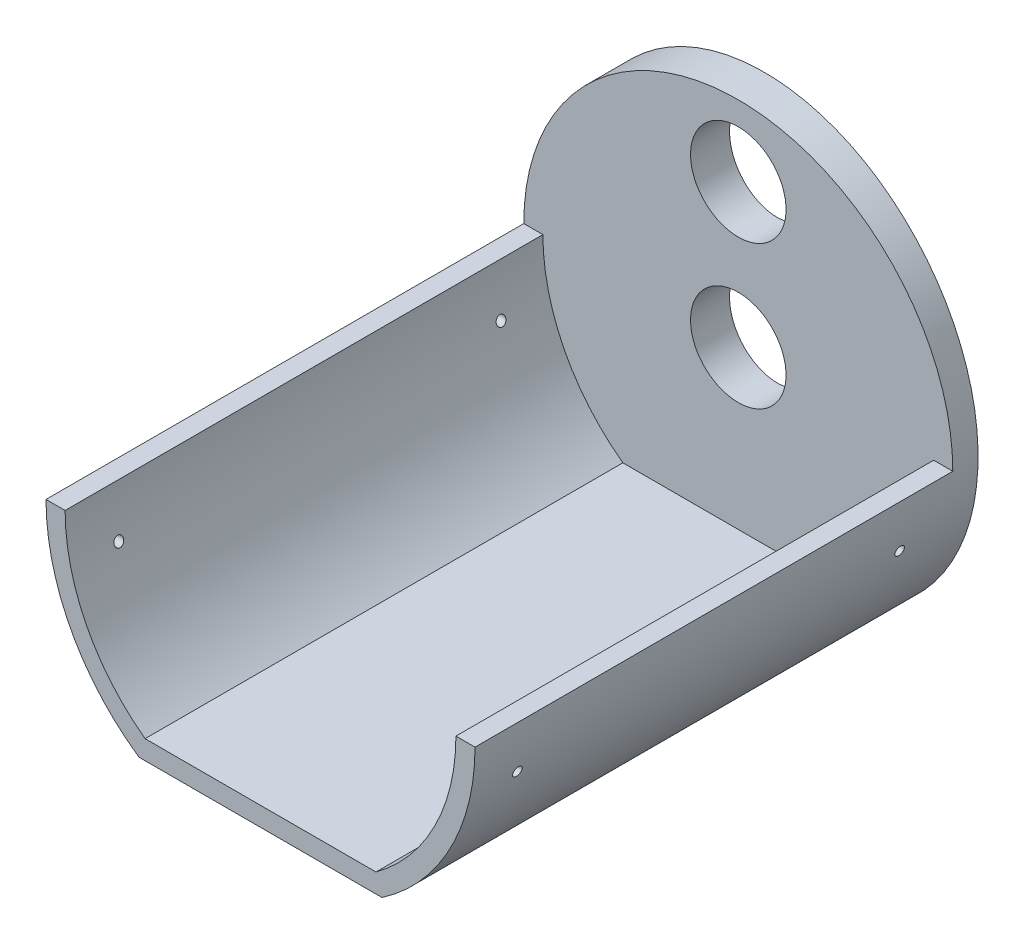
SolidWorks part; units mm, degrees
ref_plane "Front Plane" through (0, 0, 0) normal (0, 0, 1) x (1, 0, 0)
ref_plane "Top Plane" through (0, 0, 0) normal (0, 1, 0) x (1, 0, 0)
ref_plane "Right Plane" through (0, 0, 0) normal (1, 0, 0) x (0, 0, -1)
sketch "Sketch1" plane through (0, 0, 0) normal (0, 0, 1) x (1, 0, 0)
  circle A0 centre (0, 0) radius 22.45
  dimension "D1" = 44.9
extrude "Boss-Extrude1" add sketch "Sketch1" along normal blind 5
sketch "Sketch2" plane through (0, 0, 0) normal (0, 0, -1) x (-1, 0, 0)
  line L0 (0, 0) -> (0, 15) construction
  circle A0 centre (0, 0) radius 5
  circle A1 centre (0, 15) radius 5
  dimension "D1" = 10
  dimension "D2" = 15
  dimension "D3" = 10
extrude "Cut-Extrude1" cut sketch "Sketch2" against normal blind 5
sketch "Sketch3" plane through (0, 0, 5) normal (0, 0, 1) x (1, 0, 0)
  line L1 (-12.7182, -18.5) -> (12.7182, -18.5)
  line L3 (-15.2234, -16.5) -> (15.2234, -16.5)
  line L5 (-15.2234, -16.5) -> (15.2234, -16.5) construction
  line L6 (-15.2234, -16.5) -> (15.2234, -16.5) construction
  circle A0 centre (0, 0) radius 22.45 construction
  arc A1 (-15.2234, -16.5) -> (-12.7182, -18.5) centre (0, 0) ccw
  arc A2 (12.7182, -18.5) -> (15.2234, -16.5) centre (0, 0) ccw
  point P0 (0, -16.5)
  dimension "D1" = 16.5
  dimension "D3" = 2
extrude "Boss-Extrude2" add sketch "Sketch3" along normal blind 50 contours A1 L1 A2 L3
sketch "Sketch5" plane through (0, 0, 5) normal (0, 0, 1) x (1, 0, 0)
  line L0 (-15.2234, -16.5) -> (-12.0811, -16.5)
  line L1 (-20.45, 0) -> (-22.45, 0)
  line L3 (20.45, 0) -> (22.45, 0)
  line L4 (-15.2234, -16.5) -> (15.2234, -16.5) construction
  line L6 (15.2234, -16.5) -> (12.0811, -16.5)
  line L7 (-15.2234, -16.5) -> (15.2234, -16.5) construction
  arc A3 (15.2234, -16.5) -> (22.45, 0) centre (0, 0) ccw
  arc A4 (-22.45, 0) -> (-15.2234, -16.5) centre (0, 0) ccw
  arc A5 (15.2234, -16.5) -> (-15.2234, -16.5) centre (0, 0) ccw construction
  arc A6 (-20.45, 0) -> (-13.8672, -15.0301) centre (0, 0) ccw
  arc A8 (11.5852, -16.8519) -> (13.8672, -15.0301) centre (0, 0) ccw
  arc A9 (13.8672, -15.0301) -> (-13.8672, -15.0301) centre (0, 0) ccw
  arc A10 (-13.8672, -15.0301) -> (-11.5852, -16.8519) centre (0, 0) ccw
  arc A11 (12.0811, -16.5) -> (13.8672, -15.0301) centre (0, 0) ccw
  arc A12 (13.8672, -15.0301) -> (20.45, 0) centre (0, 0) ccw
  arc A13 (-13.8672, -15.0301) -> (-12.0811, -16.5) centre (0, 0) ccw
  dimension "D1" = 2
extrude "Boss-Extrude5" add sketch "Sketch5" along normal blind 50
sketch "Sketch6" plane through (0, 0, 0) normal (0, 1, 0) x (1, 0, 0)
  line L0 (-22.45, 0) -> (22.45, 0)
  line L1 (22.45, 0) -> (22.45, -2.3531)
  line L2 (22.45, -5) -> (22.45, 0) construction
  line L3 (22.45, -2.3531) -> (-22.45, 0)
  dimension "D1" = 3
extrude "Cut-Extrude3" cut sketch "Sketch6" against normal through all both and the other way through all
sketch "Sketch7" plane through (0, 0, 0) normal (1, 0, 0) x (0, 0, -1)
  line L0 (-55, 0) -> (-5, 0) construction
  line L1 (-55, 0) -> (-55, -18.5) construction
  line L2 (-5, 22.45) -> (-5, 0) construction
  circle A0 centre (-50, -5) radius 0.5
  circle A1 centre (-10, -5) radius 0.5
  dimension "D1" = 5
  dimension "D3" = 1
  dimension "D4" = 1
  dimension "D2" = 5
  dimension "D5" = 5
  dimension "D6" = 5
extrude "Cut-Extrude4" cut sketch "Sketch7" against normal through all both and the other way through all
